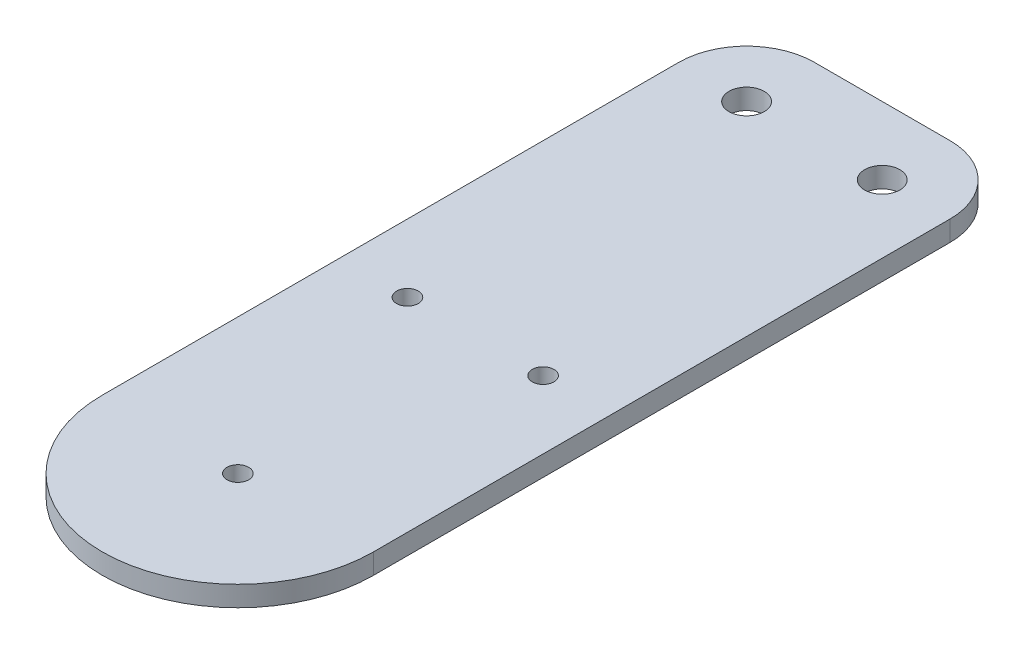
SolidWorks part; units mm, degrees
ref_plane "Front Plane" through (0, 0, 0) normal (0, 0, 1) x (1, 0, 0)
ref_plane "Top Plane" through (0, 0, 0) normal (0, 1, 0) x (1, 0, 0)
ref_plane "Right Plane" through (0, 0, 0) normal (1, 0, 0) x (0, 0, -1)
sketch "Sketch1" plane through (0, 0, 0) normal (0, 1, 0) x (1, 0, 0)
  line L0 (20, -20) -> (40, -20) construction
  line L2 (0, 0) -> (0, 95)
  line L3 (0, 95) -> (40, 95)
  line L4 (40, 0) -> (40, 95)
  line L5 (0, 0) -> (40, 0) construction
  arc A0 (0, 0) -> (40, 0) centre (20, 0) ccw
  circle A2 centre (20, 0) radius 1.6
  dimension "D3" = 115
  dimension "D2" = 3.2
  dimension "D1" = 40
extrude "Boss-Extrude1" add sketch "Sketch1" along normal blind 3
sketch "Sketch3" plane through (0, 3, 0) normal (0, 1, 0) x (1, 0, 0)
  line L0 (0, 85) -> (40, 85) construction
  line L1 (0, 0) -> (0, 95) construction
  line L2 (40, 0) -> (40, 95) construction
  line L3 (0, 95) -> (40, 95) construction
  line L4 (0, 35) -> (40, 35) construction
  circle A0 centre (10, 85) radius 2.6
  circle A1 centre (30, 85) radius 2.6
  circle A2 centre (20, 0) radius 20 construction
  arc A3 (0, 0) -> (40, 0) centre (20, 0) ccw construction
  circle A6 centre (10, 35) radius 1.6
  circle A7 centre (30, 35) radius 1.6
  point P24 (10, 35)
  point P25 (30, 35)
  point P26 (0, 0)
  point P27 (0, 0)
  dimension "D1" = 10
  dimension "D2" = 5.2
  dimension "D4" = 10
  dimension "D6" = 3.2
  dimension "D3" = 10
  dimension "D5" = 50
extrude "Cut-Extrude2" cut sketch "Sketch3" against normal blind 3
fillet "Fillet2" radius 10 2 edges at (40, 1.5, -95) (0, 1.5, -95)
